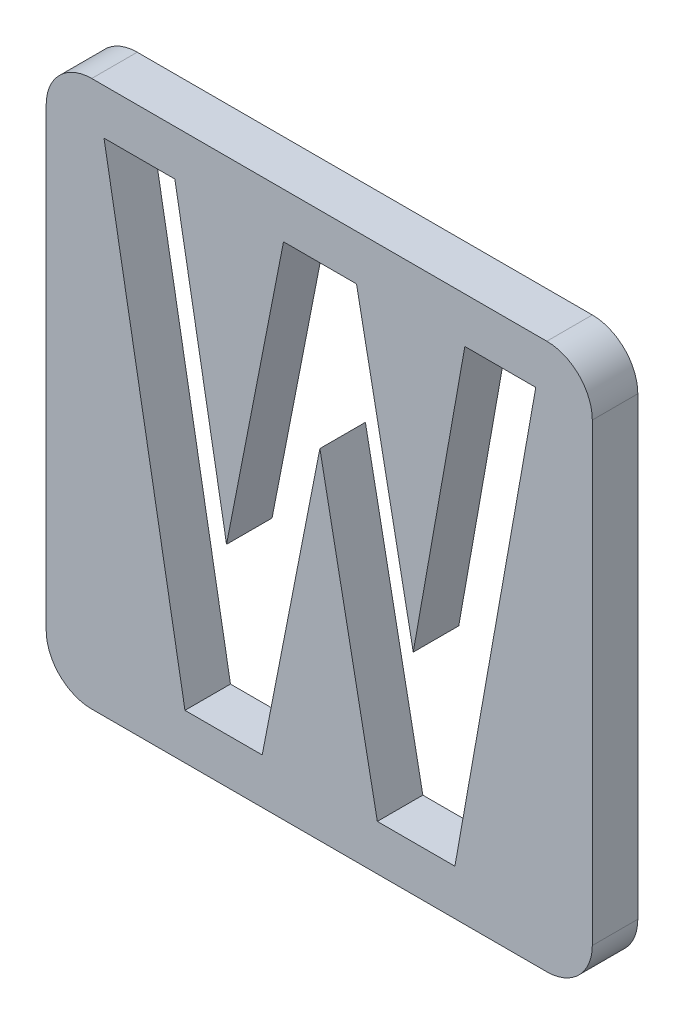
SolidWorks part; units mm, degrees
ref_plane "Front Plane" through (0, 0, 0) normal (0, 0, 1) x (1, 0, 0)
ref_plane "Top Plane" through (0, 0, 0) normal (0, 1, 0) x (1, 0, 0)
ref_plane "Right Plane" through (0, 0, 0) normal (1, 0, 0) x (0, 0, -1)
sketch "Sketch1" plane through (0, 0, 0) normal (0, 0, 1) x (1, 0, 0)
  line L1 (-50, 60) -> (50, 60)
  line L2 (-60, 50) -> (-60, -50)
  line L3 (-50, -60) -> (50, -60)
  line L4 (60, 50) -> (60, -50)
  line L5 (-60, 60) -> (60, -60) construction
  line L6 (-60, -60) -> (60, 60) construction
  arc A0 (-60, -50) -> (-50, -60) centre (-50, -50) ccw
  arc A1 (50, -60) -> (60, -50) centre (50, -50) ccw
  arc A2 (50, 60) -> (60, 50) centre (50, 50) cw
  arc A3 (-50, 60) -> (-60, 50) centre (-50, 50) ccw
  point P0 (0, 0)
  dimension "D3" = 10
  dimension "D1" = 120
  dimension "D2" = 120
extrude "Boss-Extrude1" add sketch "Sketch1" along normal blind 10 contours A3 L2 A0 L3 A1 L4 A2 L1
sketch "Sketch2" plane through (0, 0, 10) normal (0, 0, 1) x (1, 0, 0)
  line L0 (0, 0) -> (0, 40) construction
  line L1 (-50, 50) -> (50, 50) construction
  line L2 (-50, 50) -> (-50, -50) construction
  line L3 (-50, -50) -> (50, -50) construction
  line L4 (50, 50) -> (50, -50) construction
  line L5 (-50, 50) -> (50, -50) construction
  line L6 (-50, -50) -> (50, 50) construction
  line L7 (0, 40) -> (-40, 40) construction
  line L8 (-40, 40) -> (-40, 0) construction
  line L9 (-40, 0) -> (0, 0) construction
  line L11 (0, 20) -> (-20, 20) construction
  line L12 (-20, 40) -> (-20, 20) construction
  circle A0 centre (0, 40) radius 4 construction
  circle A1 centre (0, 20) radius 4 construction
  circle A2 centre (0, 0) radius 4 construction
  circle A3 centre (-20, 20) radius 4 construction
  circle A4 centre (-20, 40) radius 4 construction
  circle A5 centre (-40, 40) radius 4 construction
  circle A6 centre (0, 0) radius 4 construction
  circle A7 centre (20, 0) radius 4 construction
  circle A8 centre (40, 0) radius 4 construction
  circle A9 centre (40, 20) radius 4 construction
  circle A10 centre (40, 40) radius 4 construction
  circle A11 centre (20, 20) radius 4 construction
  circle A12 centre (0, 0) radius 4 construction
  circle A13 centre (0, -20) radius 4 construction
  circle A14 centre (0, -40) radius 4 construction
  circle A15 centre (20, -40) radius 4 construction
  circle A16 centre (40, -40) radius 4 construction
  circle A17 centre (20, -20) radius 4 construction
  circle A18 centre (0, 0) radius 4 construction
  circle A19 centre (-20, 0) radius 4 construction
  circle A20 centre (-40, 0) radius 4 construction
  circle A21 centre (-40, -20) radius 4 construction
  circle A22 centre (-40, -40) radius 4 construction
  circle A23 centre (-20, -20) radius 4 construction
  text T0 "W" font "Century Gothic" height 100
  point P0 (0, 0)
  point P55 (0, 0)
  dimension "D4" = 8
  dimension "D1" = 100
  dimension "D2" = 100
  dimension "D3" = 40
  dimension "D5" = 4
extrude "Cut-Extrude36" cut sketch "Sketch2" against normal blind 10
